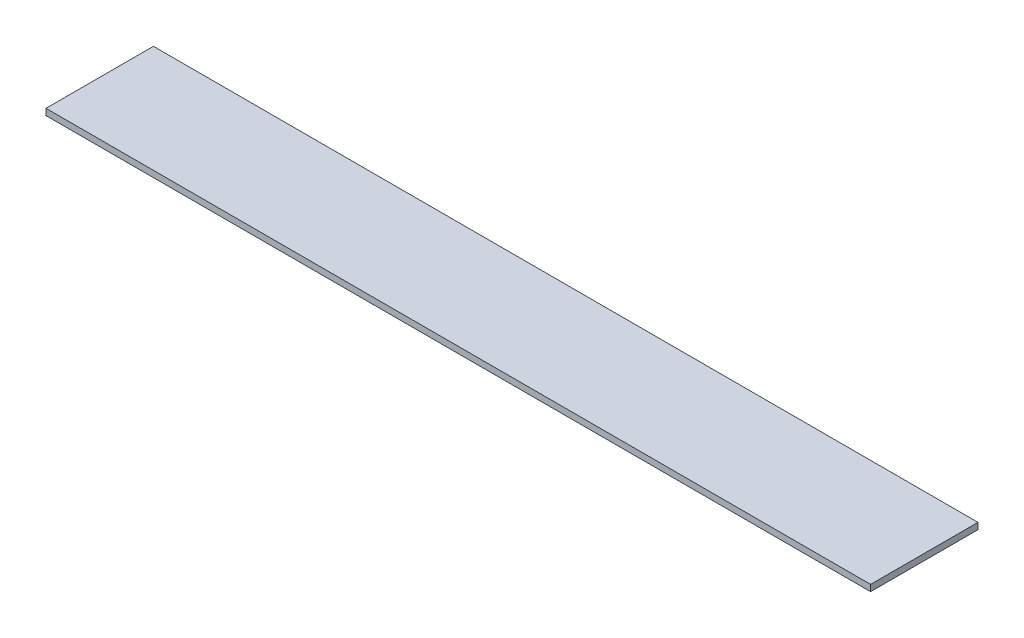
SolidWorks part; units mm, degrees
ref_plane "Alzado" through (0, 0, 0) normal (0, 0, 1) x (1, 0, 0)
ref_plane "Planta" through (0, 0, 0) normal (0, 1, 0) x (1, 0, 0)
ref_plane "Vista lateral" through (0, 0, 0) normal (1, 0, 0) x (0, 0, -1)
sketch "Croquis1" plane through (0, 0, 0) normal (0, 0, 1) x (1, 0, 0)
  line L0 (195, 1.5) -> (-195, -1.5) construction
  line L1 (-195, 1.5) -> (195, 1.5)
  line L2 (-195, 1.5) -> (-195, -1.5)
  line L3 (-195, -1.5) -> (195, -1.5)
  line L4 (195, 1.5) -> (195, -1.5)
  dimension "D1" = 390
  dimension "D2" = 3
extrude "Saliente-Extruir1" add sketch "Croquis1" along normal blind 50.8
